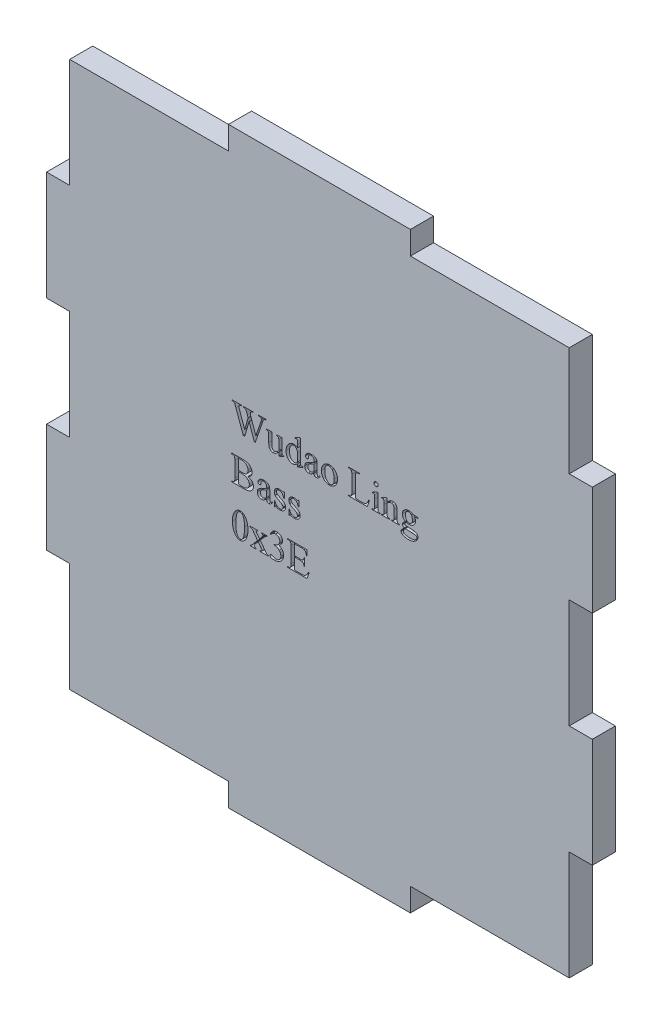
SolidWorks part; units mm, degrees
ref_plane "Front Plane" through (0, 0, 0) normal (0, 0, 1) x (1, 0, 0)
ref_plane "Top Plane" through (0, 0, 0) normal (0, 1, 0) x (1, 0, 0)
ref_plane "Right Plane" through (0, 0, 0) normal (1, 0, 0) x (0, 0, -1)
sketch "Sketch1" plane through (0, 0, 0) normal (0, 0, 1) x (1, 0, 0)
  line L0 (105.283, -33.1179) -> (105.283, -63.1179)
  line L1 (-38.367, 56.8821) -> (5.283, 56.8821)
  line L2 (105.283, -63.1179) -> (98.933, -63.1179)
  line L3 (98.933, 56.8821) -> (98.933, 26.8821)
  line L4 (-38.367, 56.8821) -> (-38.367, 26.8821)
  line L5 (98.933, -63.1179) -> (98.933, -93.1179)
  line L8 (55.283, 56.8821) -> (98.933, 56.8821)
  line L9 (5.283, 56.8821) -> (5.283, 63.2321)
  line L10 (5.283, 63.2321) -> (55.283, 63.2321)
  line L11 (55.283, 63.2321) -> (55.283, 56.8821)
  line L12 (-38.367, -63.1179) -> (-38.367, -93.1179)
  line L13 (-38.367, 26.8821) -> (-44.717, 26.8821)
  line L14 (-44.717, 26.8821) -> (-44.717, -3.1179)
  line L15 (-44.717, -3.1179) -> (-38.367, -3.1179)
  line L16 (-38.367, -3.1179) -> (-38.367, -33.1179)
  line L17 (-38.367, -33.1179) -> (-44.717, -33.1179)
  line L18 (-44.717, -33.1179) -> (-44.717, -63.1179)
  line L19 (-44.717, -63.1179) -> (-38.367, -63.1179)
  line L20 (-38.367, -93.1179) -> (5.283, -93.1179)
  line L21 (98.933, 26.8821) -> (105.283, 26.8821)
  line L22 (105.283, 26.8821) -> (105.283, -3.1179)
  line L23 (105.283, -3.1179) -> (98.933, -3.1179)
  line L24 (98.933, -3.1179) -> (98.933, -33.1179)
  line L25 (98.933, -33.1179) -> (105.283, -33.1179)
  line L29 (5.283, -93.1179) -> (5.283, -99.4679)
  line L30 (5.283, -99.4679) -> (55.283, -99.4679)
  line L31 (55.283, -99.4679) -> (55.283, -93.1179)
  line L32 (55.283, -93.1179) -> (98.933, -93.1179)
  point P5 (0, 0)
  point P41 (30.283, 4.4055)
  dimension "D2" = 6.35
  dimension "D3" = 6.35
  dimension "D4" = 30
  dimension "D5" = 150
  dimension "D6" = 30
  dimension "D7" = 30
  dimension "D8" = 30
  dimension "D9" = 30
  dimension "D10" = 6.35
  dimension "D11" = 6.35
  dimension "D12" = 6.35
  dimension "D13" = 30
  dimension "D14" = 30
  dimension "D15" = 30
  dimension "D16" = 30
  dimension "D17" = 30
extrude "Boss-Extrude1" add sketch "Sketch1" along normal blind 6.35
sketch "Sketch3" plane through (0, 0, 0) normal (0, 0, 1) x (1, 0, 0)
  text T0 "Wudao Ling\r\nBass\r\n0x3E" font "Times New Roman" height in points 28
extrude "Cut-Extrude4" cut sketch "Sketch3" along normal up to surface (6.35 mm away) up to face at (30.283, -18.1179, 6.35)
